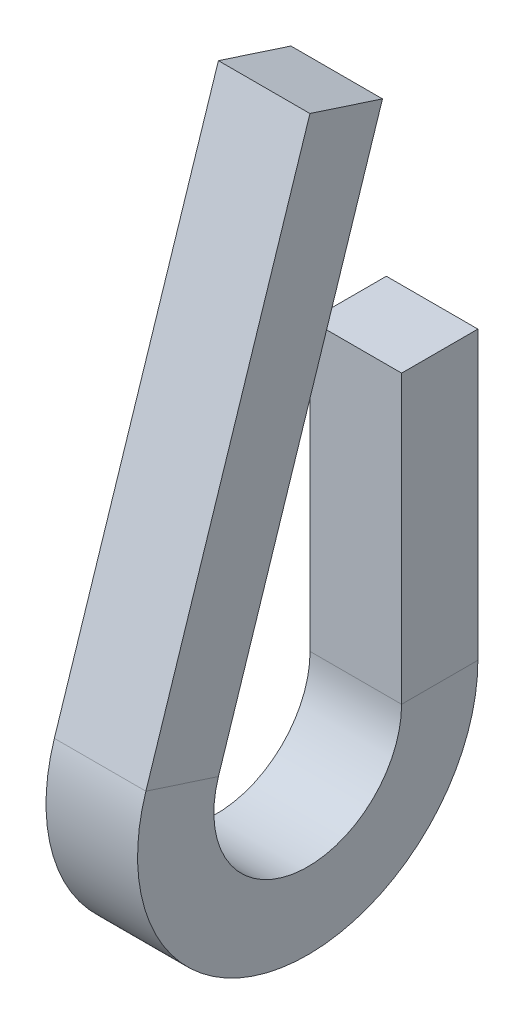
SolidWorks part; units mm, degrees
material "ABS"
ref_plane "Front" through (0, 0, 0) normal (0, 0, 1) x (1, 0, 0)
ref_plane "Top" through (0, 0, 0) normal (0, 1, 0) x (1, 0, 0)
ref_plane "Right" through (0, 0, 0) normal (1, 0, 0) x (0, 0, -1)
sketch "Esquisse1" plane through (0, 0, 0) normal (0, 1, 0) x (1, 0, 0)
  line L1 (-6, -5) -> (6, -5)
  line L2 (-6, -5) -> (-6, 5)
  line L3 (-6, 5) -> (6, 5)
  line L4 (6, -5) -> (6, 5)
  line L5 (0, 5) -> (0, -5) construction
  line L6 (-6, 0) -> (6, 0) construction
  point P0 (0, 0)
  dimension "D1" = 10
  dimension "D2" = 12
sketch "Esquisse2" plane through (0, 0, 0) normal (1, 0, 0) x (0, 0, -1)
  line L0 (0, 0) -> (0, -37.5979)
  line L1 (-33.768, -32.2496) -> (-12.263, 33.9359)
  line L2 (-11.6795, 19.5516) -> (-5.6536, 38.0972) construction
  line L4 (0, -102) -> (-88, -102) construction
  line L5 (0, 50) -> (0, -50) construction
  line L6 (-5.0356, 39.9993) -> (-3.1335, 39.3813) construction
  arc A0 (0, -37.5979) -> (-33.768, -32.2496) centre (-17.3075, -37.5979) cw
  dimension "D1" = 5
  dimension "D4" = 17.3075
  dimension "D5" = 167
  dimension "D2" = 102
  dimension "D3" = 88
  dimension "D6" = 8
sweep "Balayage1" add profiles "Esquisse1" path "Esquisse2"
